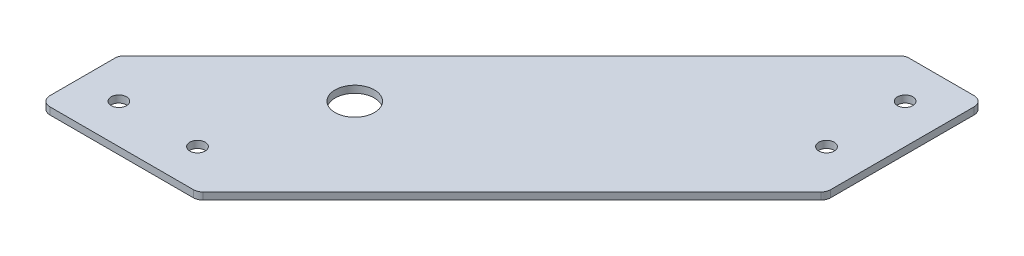
SolidWorks part; units mm, degrees
ref_plane "Front Plane" through (0, 0, 0) normal (0, 0, 1) x (1, 0, 0)
ref_plane "Top Plane" through (0, 0, 0) normal (0, 1, 0) x (1, 0, 0)
ref_plane "Right Plane" through (0, 0, 0) normal (1, 0, 0) x (0, 0, -1)
sketch "Sketch1" plane through (0, 0, 0) normal (0, 1, 0) x (1, 0, 0)
  line L0 (0, 0) -> (0, 152.4)
  line L1 (0, 152.4) -> (-25.4, 152.4)
  line L2 (-25.4, 152.4) -> (-152.4, 25.4)
  line L3 (-152.4, 25.4) -> (-152.4, 0)
  line L4 (-152.4, 0) -> (0, 0)
  circle A0 centre (-12.7, 12.7) radius 2.4892
  circle A1 centre (-38.1, 12.7) radius 2.4892
  circle A2 centre (-63.5, 12.7) radius 2.4892
  circle A3 centre (-88.9, 12.7) radius 2.4892
  circle A4 centre (-114.3, 12.7) radius 2.4892
  circle A5 centre (-12.7, 38.1) radius 2.4892
  circle A6 centre (-12.7, 63.5) radius 2.4892
  circle A7 centre (-12.7, 88.9) radius 2.4892
  circle A8 centre (-12.7, 114.3) radius 2.4892
  circle A9 centre (-139.7, 12.7) radius 2.4892
  circle A13 centre (-12.7, 139.7) radius 2.4892
  circle A17 centre (-101.6, 50.8) radius 6.35
  dimension "D4" = 12.7
  dimension "D5" = 12.7
  dimension "D8" = 12.7
  dimension "D1" = 152.4
  dimension "D2" = 25.4
  dimension "D3" = 152.4
  dimension "D9" = 101.6
  dimension "D10" = 50.8
  dimension "D11" = 25.4
  dimension "D6" = 6
  dimension "D7" = 6
extrude "Boss-Extrude2" add sketch "Sketch1" along normal mid plane 2.286
sketch "Sketch2" plane through (0, 1.143, 0) normal (0, 1, 0) x (1, 0, 0)
  line L0 (0, 0) -> (0, 101.6)
  line L1 (0, 0) -> (0, 152.4) construction
  line L2 (0, 101.6) -> (-101.6, 0)
  line L3 (-152.4, 0) -> (0, 0) construction
  line L4 (-101.6, 0) -> (0, 0)
  dimension "D1" = 45
  dimension "D2" = 101.6
  dimension "D3" = 101.6
extrude "Cut-Extrude1" cut sketch "Sketch2" against normal through all
sketch "Sketch3" plane through (0, 1.143, 0) normal (0, 1, 0) x (1, 0, 0)
  line L0 (-101.6, 0) -> (-101.6, 15.1204)
  line L1 (-101.6, 15.1204) -> (-15.6123, 101.1081)
  line L2 (-15.6123, 101.1081) -> (0, 101.6)
  line L3 (0, 101.6) -> (-101.6, 0)
extrude "Boss-Extrude3" add sketch "Sketch3" against normal blind 2.286
fillet "Fillet3" radius 3.175 6 edges at (-152.4, 0, 0) (-25.4, 0, -152.4) (0, 0, -152.4) (0, 0, -101.6) (-101.6, 0, 0) (-152.4, 0, -25.4)
equation "\"0.09inin\"=0.1"
